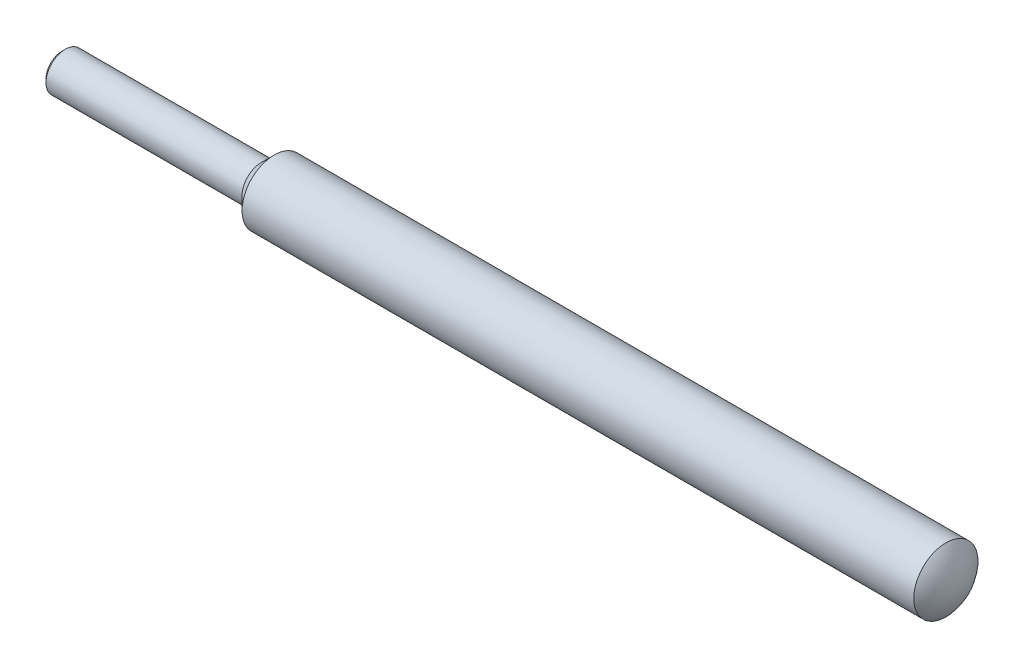
SolidWorks part; units mm, degrees
material "Plain Carbon Steel"
ref_plane "Front Plane" through (0, 0, 0) normal (0, 0, 1) x (1, 0, 0)
ref_plane "Top Plane" through (0, 0, 0) normal (0, 1, 0) x (1, 0, 0)
ref_plane "Right Plane" through (0, 0, 0) normal (1, 0, 0) x (0, 0, -1)
sketch "Sketch2" plane through (0, 0, 0) normal (0, 0, 1) x (1, 0, 0)
  line L0 (0, 0) -> (275, 0)
  line L2 (275, 10) -> (66, 10)
  line L3 (66, 10) -> (62, 6)
  line L4 (62, 6) -> (0, 6)
  line L5 (0, 6) -> (0, 0)
  line L6 (275, 0) -> (278.8197, 0)
  arc A0 (275, 10) -> (278.8197, 0) centre (263.8197, 0) cw
  dimension "D6" = 15
  dimension "D1" = 62
  dimension "D2" = 6
  dimension "D3" = 135
  dimension "D4" = 10
  dimension "D5" = 275
revolve "Revolve1" add sketch "Sketch2" angle 360 about L0
chamfer "Chamfer1" distance 1 angle 45 1 edges at (0, 0, 6)
